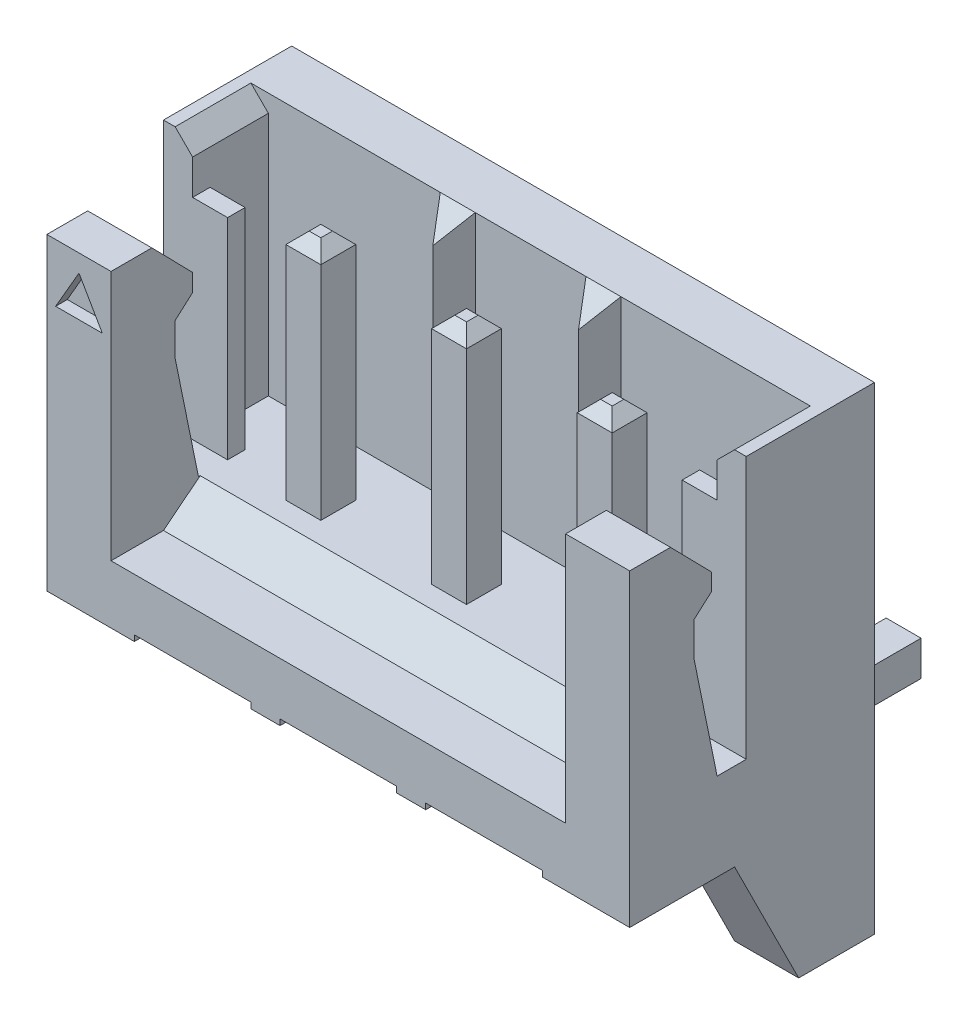
SolidWorks part; units mm, degrees
ref_plane "Спереди" through (0, 0, 0) normal (0, 0, 1) x (1, 0, 0)
ref_plane "Сверху" through (0, 0, 0) normal (0, 1, 0) x (1, 0, 0)
ref_plane "Справа" through (0, 0, 0) normal (1, 0, 0) x (0, 0, -1)
sketch "Эскиз1" plane through (0, 0, 0) normal (0, 1, 0) x (1, 0, 0)
  line L1 (0, 0) -> (10, 0)
  line L2 (0, 0) -> (0, -4.2)
  line L3 (0, -4.2) -> (10, -4.2)
  line L4 (10, 0) -> (10, -4.2)
  dimension "D1" = 10
  dimension "D2" = 4.2
extrude "Бобышка-Вытянуть1" add sketch "Эскиз1" along normal blind 6
ref_plane "Плоскость1" through (5, 0, 0) normal (1, 0, 0) x (0, 0, -1)
sketch "Эскиз2" plane through (0, 6, 0) normal (0, 1, 0) x (1, 0, 0)
  line L0 (0, 0) -> (0, -4.2) construction
  line L1 (0.5, -0.9) -> (9.5, -0.9)
  line L2 (0.5, -0.9) -> (0.5, -1.9)
  line L3 (1.1, -3.7) -> (8.9, -3.7)
  line L5 (5, 0) -> (5, -4.2) construction
  line L6 (10, 0) -> (0, 0) construction
  line L7 (0, -4.2) -> (10, -4.2) construction
  line L9 (0.5, -1.9) -> (1.1, -1.9)
  line L10 (1.1, -1.9) -> (1.1, -3.7)
  line L11 (8.9, -1.9) -> (8.9, -3.7)
  line L12 (9.5, -1.9) -> (8.9, -1.9)
  line L13 (9.5, -0.9) -> (9.5, -1.9)
  line L14 (0.5, -1.9) -> (0.5, -2.2) construction
  line L15 (0.5, -2.2) -> (1.1, -2.2) construction
  point P13 (5, -3.3)
  point P14 (5, -0.5)
  point P16 (5, -3.7)
  point P20 (5, -0.9)
  dimension "D1" = 0.5
  dimension "D2" = 0.5
  dimension "D3" = 2.8
  dimension "D4" = 0.3
  dimension "D5" = 0.6
  dimension "D6" = 1.3
extrude "Вырез-Вытянуть1" cut sketch "Эскиз2" against normal blind 5
sketch "Эскиз3" plane through (0, 0, 0) normal (-1, 0, 0) x (0, 0, 1)
  line L0 (2.2, 6) -> (2.2, 1.5)
  line L1 (0, 6) -> (4.2, 6) construction
  line L2 (2.2, 1.5) -> (2.7, 1.5)
  line L3 (2.7, 1.5) -> (3.1, 3.4596)
  line L4 (0, 6) -> (0, 0) construction
  line L5 (4.2, 5.3) -> (3.5, 5.3)
  line L6 (4.2, 6) -> (4.2, 0) construction
  line L8 (3.5, 5.3) -> (2.8, 4.5859)
  line L9 (2.8, 4.5859) -> (2.8, 4.2859)
  line L10 (2.8, 4.2859) -> (3.1, 4.0213)
  line L11 (3.1, 4.0213) -> (3.1, 3.4596)
  line L12 (2.2, 6) -> (4.2, 6)
  line L13 (4.2, 6) -> (4.2, 5.3)
  dimension "D1" = 2.2
  dimension "D2" = 4.5
  dimension "D3" = 0.7
  dimension "D4" = 0.7
  dimension "D5" = 1.4
  dimension "D6" = 1.1
  dimension "D7" = 2
  dimension "D8" = 0.4
  dimension "D9" = 1
  dimension "D10" = 0.3
  dimension "D11" = 0.5
extrude "Вырез-Вытянуть2" cut sketch "Эскиз3" against normal through all
sketch "Эскиз16" plane through (10, 0, 0) normal (1, 0, 0) x (0, 0, -1)
  line L0 (-4.2, 5.3) -> (-4.2, 0) construction
  line L1 (-4.2, 0) -> (0, 0) construction
  line L2 (-2.4, 0) -> (-1.3, -2.2)
  line L3 (-1.3, -2.2) -> (0, -2.2)
  line L4 (0, -2.2) -> (0, 0)
  line L5 (-2.4, 0) -> (0, 0)
  dimension "D1" = 2.2
  dimension "D2" = 1.3
  dimension "D3" = 1.8
extrude "Бобышка-Вытянуть6" add sketch "Эскиз16" against normal blind 1.1
mirror "Зеркальное отражение2" about plane through (5, 0, 0) normal (1, 0, 0) of "Бобышка-Вытянуть6"
sketch "Эскиз5" plane through (0, 0, 4.2) normal (0, 0, 1) x (1, 0, 0)
  line L0 (10, 5.3) -> (0, 5.3) construction
  line L1 (1.1, 5.3) -> (8.9, 5.3)
  line L2 (1.1, 5.3) -> (1.1, 1)
  line L3 (1.1, 1) -> (8.9, 1)
  line L6 (0, 5.3) -> (0, 0) construction
  line L8 (5, 1) -> (5, 5.3) construction
  line L9 (8.9, 5.3) -> (8.9, 1)
  line L11 (0, 0) -> (10, 0) construction
  line L12 (5, 0) -> (5, 5.3) construction
  line L13 (1.1, 1) -> (8.9, 1) construction
  point P14 (5, 3.15)
  dimension "D1" = 1.1
extrude "Вырез-Вытянуть3" cut sketch "Эскиз5" against normal up to next
sketch "Эскиз6" plane through (0.5, 0, 0) normal (1, 0, 0) x (0, 0, -1)
  line L0 (-0.9, 1) -> (-1.9, 1) construction
  line L2 (-3.3, 1) -> (-2.67, 1.5)
  line L3 (-2.67, 1.5) -> (-0.9, 1.5)
  line L4 (-0.9, 1) -> (-0.9, 6) construction
  line L5 (-0.9, 1.5) -> (-0.9, 1)
  line L6 (-0.9, 1) -> (-3.3, 1)
  line L8 (-4.2, 5.3) -> (-4.2, 1) construction
  dimension "D1" = 0.5
  dimension "D2" = 1.77
  dimension "D3" = 0.9
extrude "Бобышка-Вытянуть3" add sketch "Эскиз6" along normal up to next
sketch "Эскиз9" plane through (0, 6, 0) normal (0, 1, 0) x (1, 0, 0)
  line L0 (3.45, -0.9) -> (3.75, -1.3284)
  line L1 (9.5, -0.9) -> (0.5, -0.9) construction
  line L2 (3.75, -0.9) -> (3.75, -1.3284) construction
  line L3 (9.5, -0.9) -> (0.5, -0.9) construction
  line L4 (4.05, -0.9) -> (3.75, -1.3284)
  line L5 (3.45, -0.9) -> (4.05, -0.9)
  dimension "D1" = 0.6
  dimension "D2" = 35
  dimension "D3" = 2.95
extrude "Бобышка-Вытянуть5" add sketch "Эскиз9" against normal up to next
sketch "Эскиз11" plane through (0, 0, 0) normal (0, -1, 0) x (1, 0, 0)
  line L0 (0, 4.2) -> (10, 4.2) construction
  line L1 (1.5, 4.2) -> (3.5, 4.2)
  line L2 (1.5, 4.2) -> (1.5, 0)
  line L3 (1.5, 0) -> (3.5, 0)
  line L4 (3.5, 4.2) -> (3.5, 0)
  line L5 (2.5, 4.2) -> (2.5, 0) construction
  line L7 (8.9, 0) -> (1.1, 0) construction
  line L9 (2.1, 2.4) -> (2.9, 2.4)
  line L10 (2.1, 2.4) -> (2.1, 1.6)
  line L11 (2.1, 1.6) -> (2.9, 1.6)
  line L12 (2.9, 2.4) -> (2.9, 1.6)
  line L13 (2.1, 2.4) -> (2.9, 1.6) construction
  line L14 (2.1, 1.6) -> (2.9, 2.4) construction
  point P0 (2.5, 2)
  point P8 (2.5, 2)
  dimension "D1" = 2.5
  dimension "D2" = 2
  dimension "D3" = 2
  dimension "D4" = 0.8
extrude "Вырез-Вытянуть5" cut sketch "Эскиз11" against normal blind 0.1
sketch "Эскиз15" plane through (0, 0, 0) normal (0, -1, 0) x (1, 0, 0)
  line L0 (2.1, 2.4) -> (2.9, 1.6) construction
  circle A0 centre (2.5, 2) radius 0.05
  point P4 (2.5, 2)
  dimension "D1" = 0.1
extrude "Вырез-Вытянуть6" cut sketch "Эскиз15" against normal blind 0.1
pattern_linear "Линейный массив2" count 2 spacing 2.5 along (1, 0, 0) of "Бобышка-Вытянуть5"
sketch "Эскиз17" plane through (0, 0, 4.2) normal (0, 0, 1) x (1, 0, 0)
  line L0 (0.55, 5) -> (0.15, 4.3072)
  line L1 (0.15, 4.3072) -> (0.95, 4.3072)
  line L2 (0.95, 4.3072) -> (0.55, 5)
  line L3 (0.55, 5.3) -> (0.55, 0) construction
  line L4 (1.1, 5.3) -> (0, 5.3) construction
  line L5 (0, 0) -> (1.5, 0) construction
  dimension "D1" = 0.8
  dimension "D2" = 0.3
extrude "Вырез-Вытянуть7" cut sketch "Эскиз17" against normal blind 0.2
sketch "Эскиз7" plane through (0, 0, 0) normal (0, -1, 0) x (1, 0, 0)
  line L0 (10, 0) -> (0, 0) construction
  line L1 (2.2, 2.3) -> (2.8, 2.3)
  line L2 (2.2, 2.3) -> (2.2, 1.7)
  line L3 (2.2, 1.7) -> (2.8, 1.7)
  line L4 (2.8, 2.3) -> (2.8, 1.7)
  line L5 (2.2, 2.3) -> (2.8, 1.7) construction
  line L6 (2.2, 1.7) -> (2.8, 2.3) construction
  line L7 (0, 2.4) -> (0, 4.2) construction
  point P0 (2.5, 2)
  dimension "D1" = 0.6
  dimension "D2" = 2
  dimension "D3" = 2.5
extrude "Бобышка-Вытянуть4" add sketch "Эскиз7" against normal blind 5.5
sketch "Эскиз18" plane through (0, 0, 0) normal (0, -1, 0) x (1, 0, 0)
  line L1 (2.2, 1.7) -> (2.8, 1.7)
  line L2 (2.2, 1.7) -> (2.2, 2.3)
  line L3 (2.2, 2.3) -> (2.8, 2.3)
  line L4 (2.8, 1.7) -> (2.8, 2.3)
  line L5 (2.2, 1.7) -> (2.8, 2.3) construction
  line L6 (2.2, 2.3) -> (2.8, 1.7) construction
  point P0 (2.5, 2)
sketch3d "Трехмерный эскиз1"
  line L0 (2.5, -0.7, 1.3) -> (2.5, -0.7, -3.2)
  line L1 (2.5, 6, 0) -> (2.5, 0.1, 0) construction
  line L2 (10, 6, 0) -> (0, 6, 0) construction
  line L3 (2.5, 0, 2) -> (2.5, -0.7, 2) construction
  line L4 (1.5, 0.1, 0) -> (3.5, 0.1, 0) construction
  line L5 (2.5, -0.7, 1.3) -> (2.5, -0.7, 2) construction
  arc A0 (2.5, 0, 2) -> (2.5, -0.7, 1.3) centre (2.5, 0, 1.3) cw
  point P12 (3.2, 0, 1.3)
  dimension "D1" = 6.7
  dimension "D2" = 3.2
sweep "По траектории1" add profiles "Эскиз18" path "Трехмерный эскиз1"
chamfer "Фаска6" distance 0.2 angle 45 8 edges at (2.5, 5.5, 2.3) (2.2, 5.5, 2) (2.5, 5.5, 1.7) (2.8, 5.5, 2) (2.5, -0.4, -3.2) (2.2, -0.7, -3.2) (2.5, -1, -3.2) (2.8, -0.7, -3.2)
pattern_linear "Линейный массив1" count 3 spacing 2.5 along (1, 0, 0) of "Бобышка-Вытянуть4", "Фаска6", "Вырез-Вытянуть5", "По траектории1"
sketch "Эскиз10" plane through (0.5, 0, 0) normal (1, 0, 0) x (0, 0, -1)
  line L0 (-1.4, 6) -> (-0.9, 6)
  line L1 (-0.9, 6) -> (-1.4, 5.5)
  line L4 (-0.9, 6) -> (-1.9, 6) construction
  line L7 (-2.2, 6) -> (-1.4, 6) construction
  line L8 (-1.4, 5.5) -> (-1.4, 6)
  dimension "D1" = 45
  dimension "D3" = 0.5
  dimension "D4" = 0.8
extrude "Вырез-Вытянуть4" cut sketch "Эскиз10" along normal up to surface (9 mm away) contours L1 L8 L0 up to face at (9.5, 3.75, 1.4)
sketch "Эскиз20" plane through (0, 6, 0) normal (0, 1, 0) x (1, 0, 0)
  line L1 (0.5, -1.9) -> (1.1, -1.9)
  line L2 (0.5, -1.9) -> (0.5, -2.2)
  line L3 (0.5, -2.2) -> (1.1, -2.2)
  line L4 (1.1, -1.9) -> (1.1, -2.2)
extrude "Вырез-Вытянуть9" cut sketch "Эскиз20" against normal blind 0.9
mirror "Зеркальное отражение3" about plane through (5, 0, 0) normal (1, 0, 0) of "Вырез-Вытянуть9"
chamfer "Фаска5" distance 0.3 angle 45 2 edges at (9.5, 6, 1.55) (0.5, 6, 1.55)
sketch "Эскиз19" plane through (0, 0, 0) normal (0, 0, -1) x (-1, 0, 0)
  line L0 (-2.5, -1) -> (-2.5, -0.4) construction
  line L1 (-2.8, -1) -> (-2.2, -1) construction
  line L2 (-2.8, -1) -> (-2.8, -0.4) construction
  line L3 (-2.8, -0.4) -> (-2.2, -0.4) construction
  line L4 (-2.2, -1) -> (-2.2, -0.4) construction
  circle A0 centre (-2.5, -0.7) radius 0.05
  point P8 (-2.5, -0.7)
  dimension "D1" = 0.1
extrude "Вырез-Вытянуть8" cut sketch "Эскиз19" along normal up to surface (3.2 mm away) up to face at (2.5, -0.7, -3.2)
ref_point "Точка1"
equation "\"PINS\"= 3"
equation "\"D1@Линейный массив2\"= \"GUIDE_MASS\""
equation "\"PIN_MASS\"= \"PINS\""
equation "\"D1@Линейный массив1\"=\"PIN_MASS\""
equation "\"GUIDE_MASS\"= \"PINS\" - 1"
equation "\"D1@Эскиз1\"= 5 + ( 2.5 * ( \"PIN_MASS\" - 1 ) )"
